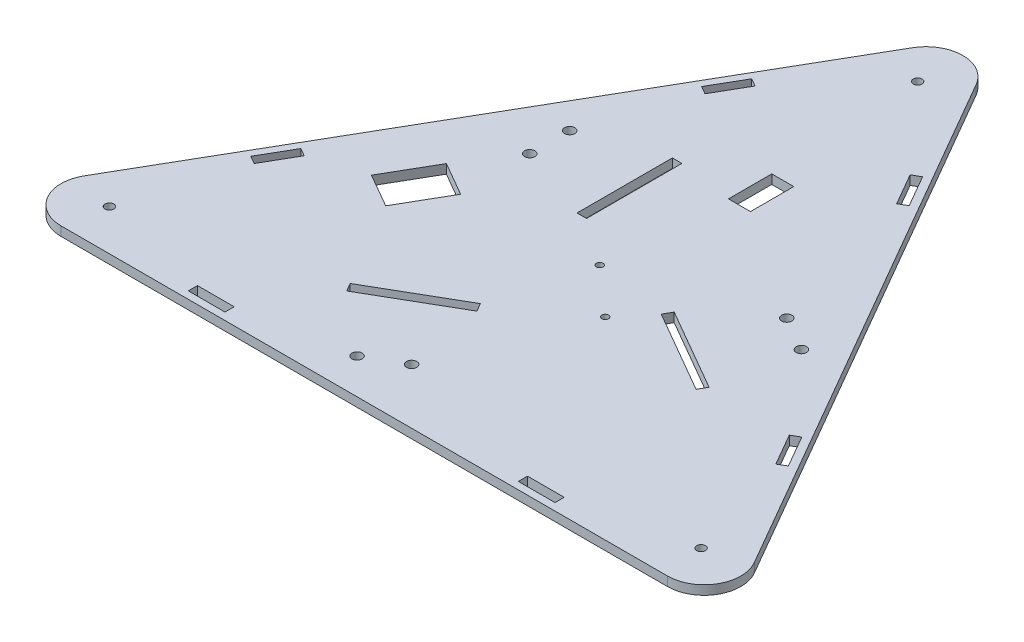
SolidWorks part; units mm, degrees
ref_plane "Front Plane" through (0, 0, 0) normal (0, 0, 1) x (1, 0, 0)
ref_plane "Top Plane" through (0, 0, 0) normal (0, 1, 0) x (1, 0, 0)
ref_plane "Right Plane" through (0, 0, 0) normal (1, 0, 0) x (0, 0, -1)
sketch "Sketch1" plane through (0, 0, 0) normal (0, 1, 0) x (1, 0, 0)
  line L1 (0, 146.647) -> (-127, -73.3235)
  line L2 (-127, -73.3235) -> (127, -73.3235)
  line L3 (127, -73.3235) -> (0, 146.647)
  circle A0 centre (0, 0) radius 73.3235 construction
  dimension "D1" = 254
extrude "Boss-Extrude1" add sketch "Sketch1" along normal blind 3.175
sketch "Sketch2" plane through (0, 3.175, 0) normal (0, 1, 0) x (1, 0, 0)
  line L0 (0, 19.8896) -> (0, 146.647)
  line L1 (34.4497, 19.8896) -> (-34.4497, 19.8896)
  line L2 (-34.4497, 19.8896) -> (0, -39.7791)
  line L3 (0, -39.7791) -> (34.4497, 19.8896)
  line L4 (-17.2249, -9.9448) -> (-127, -73.3235)
  line L5 (17.2249, -9.9448) -> (127, -73.3235)
  line L6 (0, 146.647) -> (-127, -73.3235) construction
  line L7 (-63.802, 10.7387) -> (-56.8738, 6.7387)
  line L8 (-63.802, 10.7387) -> (-73.302, -5.7158)
  line L9 (-73.302, -5.7158) -> (-66.3738, -9.7158)
  line L10 (-56.8738, 6.7387) -> (-66.3738, -9.7158)
  line L11 (-127, -73.3235) -> (127, -73.3235) construction
  circle A0 centre (0, 0) radius 19.8896 construction
  line B0 (-7.4459, -26.8825) -> (-36.042, -43.3925)
  line B1 (-7.4459, -26.8825) -> (8.5475, -54.5838)
  line B2 (8.5475, -54.5838) -> (-20.0487, -71.0938)
  line B3 (-36.042, -43.3925) -> (-20.0487, -71.0938)
  line B4 (-7.4459, -26.8825) -> (-36.042, -43.3925)
  line B5 (-7.4459, -26.8825) -> (-9.0969, -24.0229)
  line B6 (-9.0969, -24.0229) -> (-37.693, -40.5329)
  line B7 (-36.042, -43.3925) -> (-37.693, -40.5329)
  line B8 (-9.0969, -24.0229) -> (-37.693, -40.5329)
  line B9 (-9.0969, -24.0229) -> (-17.2249, -9.9448)
  line B10 (-17.2249, -9.9448) -> (-45.821, -26.4548)
  line B11 (-37.693, -40.5329) -> (-45.821, -26.4548)
  circle B12 centre (-2.7732, -54.1663) radius 1.778
  circle B13 centre (-7.3295, -60.1042) radius 1.3525
  circle B14 centre (-14.7499, -61.0811) radius 1.778
  circle B15 centre (-20.6878, -56.5248) radius 1.3525
  circle B16 centre (-21.6647, -49.1043) radius 1.778
  circle B17 centre (-17.1085, -43.1664) radius 1.3525
  circle B18 centre (-9.688, -42.1895) radius 1.778
  circle B19 centre (-3.7501, -46.7458) radius 1.3525
  line B20 (-19.558, 19.8896) -> (-19.558, 52.9096)
  line B21 (-19.558, 19.8896) -> (-51.5447, 19.8896)
  line B22 (-51.5447, 19.8896) -> (-51.5447, 52.9096)
  line B23 (-19.558, 52.9096) -> (-51.5447, 52.9096)
  line B24 (-19.558, 19.8896) -> (-19.558, 52.9096)
  line B25 (-19.558, 19.8896) -> (-16.256, 19.8896)
  line B26 (-16.256, 19.8896) -> (-16.256, 52.9096)
  line B27 (-19.558, 52.9096) -> (-16.256, 52.9096)
  line B28 (-16.256, 19.8896) -> (-16.256, 52.9096)
  line B29 (-16.256, 19.8896) -> (0, 19.8896)
  line B30 (0, 19.8896) -> (0, 52.9096)
  line B31 (-16.256, 52.9096) -> (0, 52.9096)
  circle B32 centre (-45.5228, 29.4848) radius 1.778
  circle B33 centre (-48.387, 36.3996) radius 1.3525
  circle B34 centre (-45.5228, 43.3144) radius 1.778
  circle B35 centre (-38.608, 46.1786) radius 1.3525
  circle B36 centre (-31.6932, 43.3144) radius 1.778
  circle B37 centre (-28.829, 36.3996) radius 1.3525
  circle B38 centre (-31.6932, 29.4848) radius 1.778
  circle B39 centre (-38.608, 26.6206) radius 1.3525
  line B40 (27.0039, 6.9929) -> (55.6, -9.5171)
  line B41 (27.0039, 6.9929) -> (42.9972, 34.6942)
  line B42 (42.9972, 34.6942) -> (71.5934, 18.1842)
  line B43 (55.6, -9.5171) -> (71.5934, 18.1842)
  line B44 (27.0039, 6.9929) -> (55.6, -9.5171)
  line B45 (27.0039, 6.9929) -> (25.3529, 4.1333)
  line B46 (25.3529, 4.1333) -> (53.949, -12.3767)
  line B47 (55.6, -9.5171) -> (53.949, -12.3767)
  line B48 (25.3529, 4.1333) -> (53.949, -12.3767)
  line B49 (25.3529, 4.1333) -> (17.2249, -9.9448)
  line B50 (17.2249, -9.9448) -> (45.821, -26.4548)
  line B51 (53.949, -12.3767) -> (45.821, -26.4548)
  circle B52 centre (48.296, 24.6815) radius 1.778
  circle B53 centre (55.7165, 23.7046) radius 1.3525
  circle B54 centre (60.2727, 17.7667) radius 1.778
  circle B55 centre (59.2958, 10.3462) radius 1.3525
  circle B56 centre (53.3579, 5.7899) radius 1.778
  circle B57 centre (45.9375, 6.7669) radius 1.3525
  circle B58 centre (41.3812, 12.7047) radius 1.778
  circle B59 centre (42.3581, 20.1252) radius 1.3525
  dimension "D1" = 19
  dimension "D2" = 8
  dimension "D3" = 12.7
sketch_block_instance "Servo_Brackets_BlockV3-1"
sketch_block "Servo_Brackets_BlockV3" parameters "D1"=3.302, "D2"=16.256
sketch_block_instance "Servo_Brackets_BlockV3-2"
sketch_block_instance "Servo_Brackets_BlockV3-3"
extrude "Cut-Extrude1" cut sketch "Sketch2" against normal through all contours B27 B20 L1 B26 | B34 | B32 | B14 | B12 | B7 B0 L2 B6 | B47 B40 L3 B46 | B52 | B54
sketch "Sketch3" plane through (0, 3.175, 0) normal (0, 1, 0) x (1, 0, 0)
  line L0 (63.5, 36.6617) -> (51.4016, 29.6767)
  line L1 (22.225, 108.1521) -> (104.775, -34.8287)
  line L2 (22.225, 108.1521) -> (10.1266, 101.1671)
  line L3 (10.1266, 101.1671) -> (92.6766, -41.8137)
  line L4 (104.775, -34.8287) -> (92.6766, -41.8137)
  line L5 (-63.5, 36.6617) -> (-51.4016, 29.6767)
  line L6 (-104.775, -34.8287) -> (-22.225, 108.1521)
  line L7 (-104.775, -34.8287) -> (-92.6766, -41.8137)
  line L8 (-92.6766, -41.8137) -> (-10.1266, 101.1671)
  line L9 (-22.225, 108.1521) -> (-10.1266, 101.1671)
  line L10 (0, -59.3535) -> (0, -73.3235)
  line L11 (-82.55, -59.3535) -> (82.55, -59.3535)
  line L12 (-82.55, -59.3535) -> (-82.55, -73.3235)
  line L13 (-82.55, -73.3235) -> (82.55, -73.3235)
  line L14 (82.55, -59.3535) -> (82.55, -73.3235)
  line L15 (127, -73.3235) -> (0, 146.647) construction
  line L16 (0, 146.647) -> (-127, -73.3235) construction
  line L17 (-127, -73.3235) -> (127, -73.3235) construction
  line L18 (-22.225, 108.1521) -> (22.225, 108.1521)
  line L19 (-104.775, -34.8287) -> (-82.55, -73.3235)
  line L20 (104.775, -34.8287) -> (82.55, -73.3235)
  circle A0 centre (102.4613, -59.1561) radius 1.524
  circle A1 centre (0, 118.3121) radius 1.524
  circle A2 centre (-102.4613, -59.1561) radius 1.524
  dimension "D7" = 3.048
  dimension "D20" = 10.16
  dimension "D1" = 165.1
  dimension "D2" = 10.16
  dimension "D3" = 165.1
  dimension "D4" = 13.97
  dimension "D6" = 13.97
  dimension "D21" = 10.16
extrude "Cut-Extrude2" cut sketch "Sketch3" against normal through all contours A1 | A2 | A0
sketch "Sketch4" plane through (0, 3.175, 0) normal (0, 1, 0) x (1, 0, 0)
  line L1 (16.51, -6.3973) -> (16.51, 8.2077) construction
  line L2 (16.51, -6.3973) -> (0, -6.3973) construction
  line L3 (0, -6.3973) -> (0, 8.2077) construction
  line L4 (16.51, 8.2077) -> (0, 8.2077) construction
  circle A0 centre (0, 8.2077) radius 1.143
  circle A1 centre (16.51, -6.3973) radius 1.143
  dimension "D3" = 2.286
  dimension "D4" = 2.286
  dimension "D1" = 14.605
  dimension "D2" = 16.51
extrude "Cut-Extrude3" cut sketch "Sketch4" against normal through all
fillet "Fillet1" radius 12.7 3 edges at (0, 1.5875, -146.647) (127, 1.5875, 73.3235) (-127, 1.5875, 73.3235)
sketch "Sketch5" plane through (0, 3.175, 0) normal (0, 1, 0) x (1, 0, 0)
  line L0 (-10.9985, 127.597) -> (-116.0015, -54.2735) construction
  line L1 (116.0015, -54.2735) -> (10.9985, 127.597) construction
  line L2 (-105.003, -73.3235) -> (105.003, -73.3235) construction
  line B0 (61.1819, 35.5969) -> (58.4322, 34.0094)
  line B1 (102.8822, -42.9803) -> (105.6319, -41.3928)
  line B2 (102.8822, -42.9803) -> (13.9822, 110.9991)
  line B3 (13.9822, 110.9991) -> (16.7319, 112.5866)
  line B4 (105.6319, -41.3928) -> (16.7319, 112.5866)
  line B5 (92.9319, -19.3957) -> (90.1822, -20.9832)
  line B6 (92.9319, -19.3957) -> (86.5819, -8.3972)
  line B7 (86.5819, -8.3972) -> (83.8322, -9.9847)
  line B8 (90.1822, -20.9832) -> (83.8322, -9.9847)
  line B9 (35.7819, 79.591) -> (33.0322, 78.0035)
  line B10 (35.7819, 79.591) -> (29.4319, 90.5895)
  line B11 (29.4319, 90.5895) -> (26.6822, 89.002)
  line B12 (33.0322, 78.0035) -> (26.6822, 89.002)
  line B13 (105.6319, -41.3928) -> (107.8316, -40.1228)
  line B14 (105.6319, -41.3928) -> (16.7319, 112.5866)
  line B15 (16.7319, 112.5866) -> (18.9316, 113.8566)
  line B16 (107.8316, -40.1228) -> (18.9316, 113.8566)
  line B17 (0, -70.7835) -> (0, -67.6085)
  line B18 (-88.9, -67.6085) -> (-88.9, -70.7835)
  line B19 (-88.9, -67.6085) -> (88.9, -67.6085)
  line B20 (88.9, -67.6085) -> (88.9, -70.7835)
  line B21 (-88.9, -70.7835) -> (88.9, -70.7835)
  line B22 (-63.5, -70.7835) -> (-63.5, -67.6085)
  line B23 (-63.5, -70.7835) -> (-50.8, -70.7835)
  line B24 (-50.8, -70.7835) -> (-50.8, -67.6085)
  line B25 (-63.5, -67.6085) -> (-50.8, -67.6085)
  line B26 (50.8, -70.7835) -> (50.8, -67.6085)
  line B27 (50.8, -70.7835) -> (63.5, -70.7835)
  line B28 (63.5, -70.7835) -> (63.5, -67.6085)
  line B29 (50.8, -67.6085) -> (63.5, -67.6085)
  line B30 (-88.9, -70.7835) -> (-88.9, -73.3235)
  line B31 (-88.9, -70.7835) -> (88.9, -70.7835)
  line B32 (88.9, -70.7835) -> (88.9, -73.3235)
  line B33 (-88.9, -73.3235) -> (88.9, -73.3235)
  line B34 (-61.3003, 35.3917) -> (-58.5507, 33.8042)
  line B35 (-14.1007, 110.7939) -> (-16.8503, 112.3814)
  line B36 (-14.1007, 110.7939) -> (-103.0007, -43.1854)
  line B37 (-103.0007, -43.1854) -> (-105.7503, -41.5979)
  line B38 (-16.8503, 112.3814) -> (-105.7503, -41.5979)
  line B39 (-29.5503, 90.3844) -> (-26.8007, 88.7969)
  line B40 (-29.5503, 90.3844) -> (-35.9003, 79.3858)
  line B41 (-35.9003, 79.3858) -> (-33.1507, 77.7983)
  line B42 (-26.8007, 88.7969) -> (-33.1507, 77.7983)
  line B43 (-86.7003, -8.6023) -> (-83.9507, -10.1898)
  line B44 (-86.7003, -8.6023) -> (-93.0503, -19.6009)
  line B45 (-93.0503, -19.6009) -> (-90.3007, -21.1884)
  line B46 (-83.9507, -10.1898) -> (-90.3007, -21.1884)
  line B47 (-16.8503, 112.3814) -> (-19.05, 113.6514)
  line B48 (-16.8503, 112.3814) -> (-105.7503, -41.5979)
  line B49 (-105.7503, -41.5979) -> (-107.95, -40.3279)
  line B50 (-19.05, 113.6514) -> (-107.95, -40.3279)
sketch_block_instance "Base_Side_Block-1"
sketch_block "Base_Side_Block" parameters "D1"=177.8, "D2"=3.175, "D3"=25.4, "D4"=25.4, "D5"=12.7, "D6"=12.7, "D7"=2.54
sketch_block_instance "Base_Side_Block-2"
sketch_block_instance "Base_Side_Block-3"
extrude "Cut-Extrude4" cut sketch "Sketch5" against normal through all contours B21 B24 B19 B22 | B21 B28 B19 B26 | B4 B7 B2 B5 | B4 B11 B2 B9 | B38 B41 B36 B39 | B38 B45 B36 B43
sketch "Sketch6" plane through (0, 3.175, 0) normal (0, 1, 0) x (1, 0, 0)
  line L0 (-10.9985, 127.597) -> (-116.0015, -54.2735) construction
  line L1 (-54.8299, -11.0968) -> (-45.3299, 5.3577)
  line L2 (-54.8299, -11.0968) -> (-66.4883, -4.3658)
  line L3 (-66.4883, -4.3658) -> (-56.9883, 12.0887)
  line L4 (-45.3299, 5.3577) -> (-56.9883, 12.0887)
  dimension "D1" = 13.462
  dimension "D2" = 19
extrude "Cut-Extrude5" cut sketch "Sketch6" against normal through all
sketch "Sketch9" plane through (0, 3.175, 0) normal (0, 1, 0) x (1, 0, 0)
  line L0 (-16.256, 19.8896) -> (-16.256, 52.9096) construction
  line L1 (2.4441, 65.3363) -> (10.0641, 65.3363)
  line L2 (2.4441, 65.3363) -> (2.4441, 50.3363)
  line L3 (2.4441, 50.3363) -> (10.0641, 50.3363)
  line L4 (10.0641, 65.3363) -> (10.0641, 50.3363)
  dimension "D1" = 15
  dimension "D2" = 7.62
extrude "Cut-Extrude8" cut sketch "Sketch9" against normal through all
